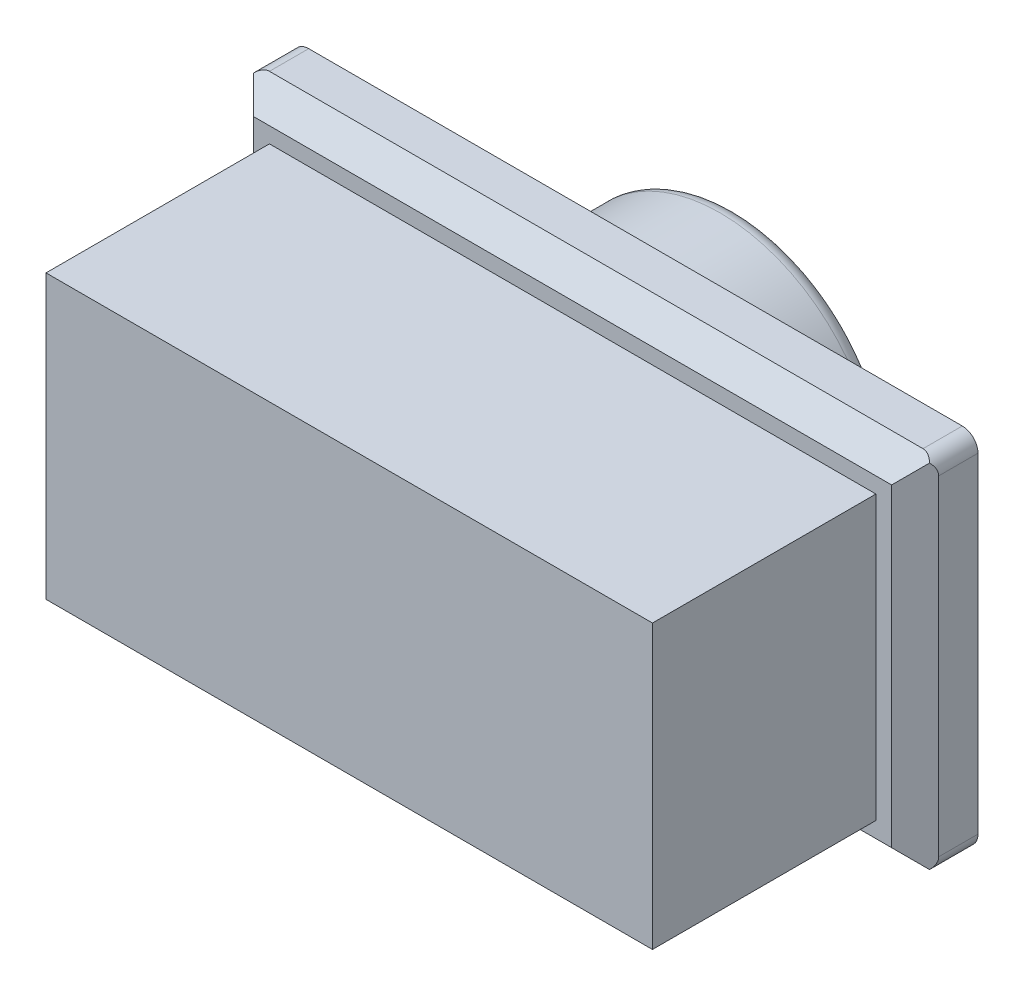
SolidWorks part; units mm, degrees
ref_plane "Front Plane" through (0, 0, 0) normal (0, 0, 1) x (1, 0, 0)
ref_plane "Top Plane" through (0, 0, 0) normal (0, 1, 0) x (1, 0, 0)
ref_plane "Right Plane" through (0, 0, 0) normal (1, 0, 0) x (0, 0, -1)
sketch "Sketch1" plane through (0, 0, 0) normal (0, 0, 1) x (1, 0, 0)
  line L0 (-4.826, 2.25) -> (4.826, 2.25)
  line L1 (-4.826, 2.25) -> (-4.826, -2.25)
  line L2 (-4.826, -2.25) -> (4.826, -2.25)
  line L3 (4.826, 2.25) -> (4.826, -2.25)
  line L4 (0, 2.25) -> (0, -2.25) construction
  line L5 (-4.826, 0) -> (4.826, 0) construction
  dimension "D1" = 9.652
  dimension "D2" = 4.5
extrude "Button Base" add sketch "Sketch1" along normal blind 3.556
sketch "Sketch2" plane through (0, 0, 0) normal (0, 0, -1) x (-1, 0, 0)
  line L8 (5.451, -2.875) -> (5.451, 2.875)
  line L9 (5.451, 2.875) -> (-5.451, 2.875)
  line L10 (-5.451, 2.875) -> (-5.451, -2.875)
  line L11 (-5.451, -2.875) -> (5.451, -2.875)
  line L12 (5.451, -2.875) -> (5.451, 2.875)
  line L13 (5.451, 2.875) -> (-5.451, 2.875)
  line L14 (-5.451, 2.875) -> (-5.451, -2.875)
  line L15 (-5.451, -2.875) -> (5.451, -2.875)
  dimension "D1" = 0.625
extrude "Guide" add sketch "Sketch2" along normal blind 1
sketch "Sketch3" plane through (0, 0, -1) normal (0, 0, -1) x (-1, 0, 0)
  circle A0 centre (0, 0) radius 2.54
  dimension "D1" = 5.08
extrude "Arm" add sketch "Sketch3" along normal blind 1.6002
chamfer "Chamfer1" distance 0.375 angle 45 4 edges at (0, -2.875, 0) (-5.451, 0, 0) (0, 2.875, 0) (5.451, 0, 0)
fillet "Fillet1" radius 0.25 4 edges at (-5.451, -2.875, -0.6875) (5.451, -2.875, -0.6875) (5.451, 2.875, -0.6875) (-5.451, 2.875, -0.6875)
sketch "Sketch4" plane through (0, 0, -2.6002) normal (0, 0, -1) x (-1, 0, 0)
  line L4 (-1.258, 0) -> (0, 0) construction
  line L12 (-1.258, 1.7272) -> (-1.258, -1.7272)
  line L13 (1.282, 1.7272) -> (-1.258, 1.7272)
  line L14 (1.282, -1.7272) -> (1.282, 1.7272)
  line L15 (-1.258, -1.7272) -> (1.282, -1.7272)
  dimension "D1" = 3.4544
  dimension "D2" = 2.54
  dimension "D3" = 1.282
extrude "Cut-Extrude1" [suppressed] cut sketch "Sketch4" against normal blind 2.54
fillet "Fillet2" radius 0.254 1 edges at (-2.54, 0, -2.6002)
